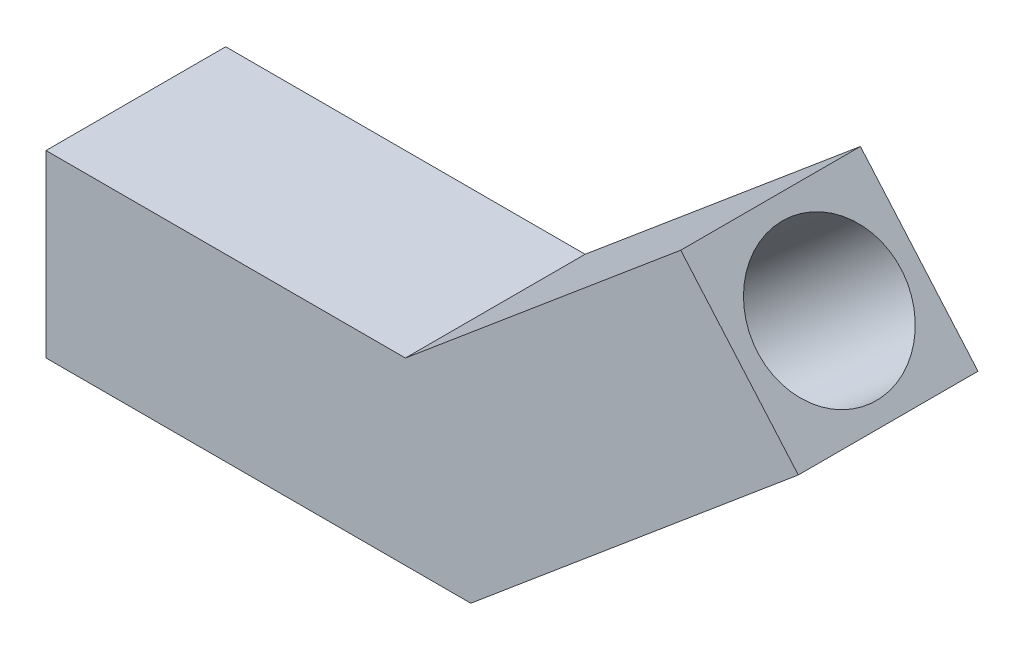
SolidWorks part; units mm, degrees
ref_plane "Front Plane" through (0, 0, 0) normal (0, 0, 1) x (1, 0, 0)
ref_plane "Top Plane" through (0, 0, 0) normal (0, 1, 0) x (1, 0, 0)
ref_plane "Right Plane" through (0, 0, 0) normal (1, 0, 0) x (0, 0, -1)
sketch "Sketch1" plane through (0, 0, 0) normal (0, 0, 1) x (1, 0, 0)
  line L0 (-5, 0) -> (0, 0)
  line L1 (0, 0) -> (3.8302, 3.2139)
  line L2 (-5, 0) -> (-5, -2.5)
  line L3 (-5, -2.5) -> (0.9095, -2.5)
  line L4 (0.9095, -2.5) -> (5.466, 1.3234)
  line L5 (5.466, 1.3234) -> (3.8302, 3.2139)
  dimension "D1" = 5
  dimension "D2" = 5
  dimension "D3" = 140
  dimension "D4" = 2.5
  dimension "D5" = 2.5
extrude "Boss-Extrude1" add sketch "Sketch1" along normal blind 2.5
sketch "Sketch2" plane through (3.7807, 3.2711, 0) normal (0.7562, 0.6543, 0) x (0, 0, -1)
  line L0 (-2.5, -1.3256) -> (0, -1.3256) construction
  line L1 (-2.5, -2.5756) -> (-2.5, -0.0756) construction
  line L2 (0, -2.5756) -> (0, -0.0756) construction
  line L3 (-1.25, -0.0756) -> (-1.25, -2.5756) construction
  line L4 (-2.5, -0.0756) -> (0, -0.0756) construction
  line L5 (-2.5, -2.5756) -> (0, -2.5756) construction
  circle A0 centre (-1.25, -1.3256) radius 1
  dimension "D1" = 2
extrude "Cut-Extrude1" cut sketch "Sketch2" against normal blind 5
sketch "Sketch3" plane through (-5, 0, 0) normal (-1, 0, 0) x (0, 0, 1)
  line L0 (1.25, 0) -> (1.25, -2.5) construction
  line L1 (2.5, 0) -> (0, 0) construction
  line L2 (2.5, -2.5) -> (0, -2.5) construction
  line L3 (0, -1.25) -> (2.5, -1.25) construction
  line L4 (0, 0) -> (0, -2.5) construction
  line L5 (2.5, 0) -> (2.5, -2.5) construction
  circle A0 centre (1.25, -1.25) radius 1
  dimension "D1" = 2
extrude "Cut-Extrude2" cut sketch "Sketch3" against normal blind 5
